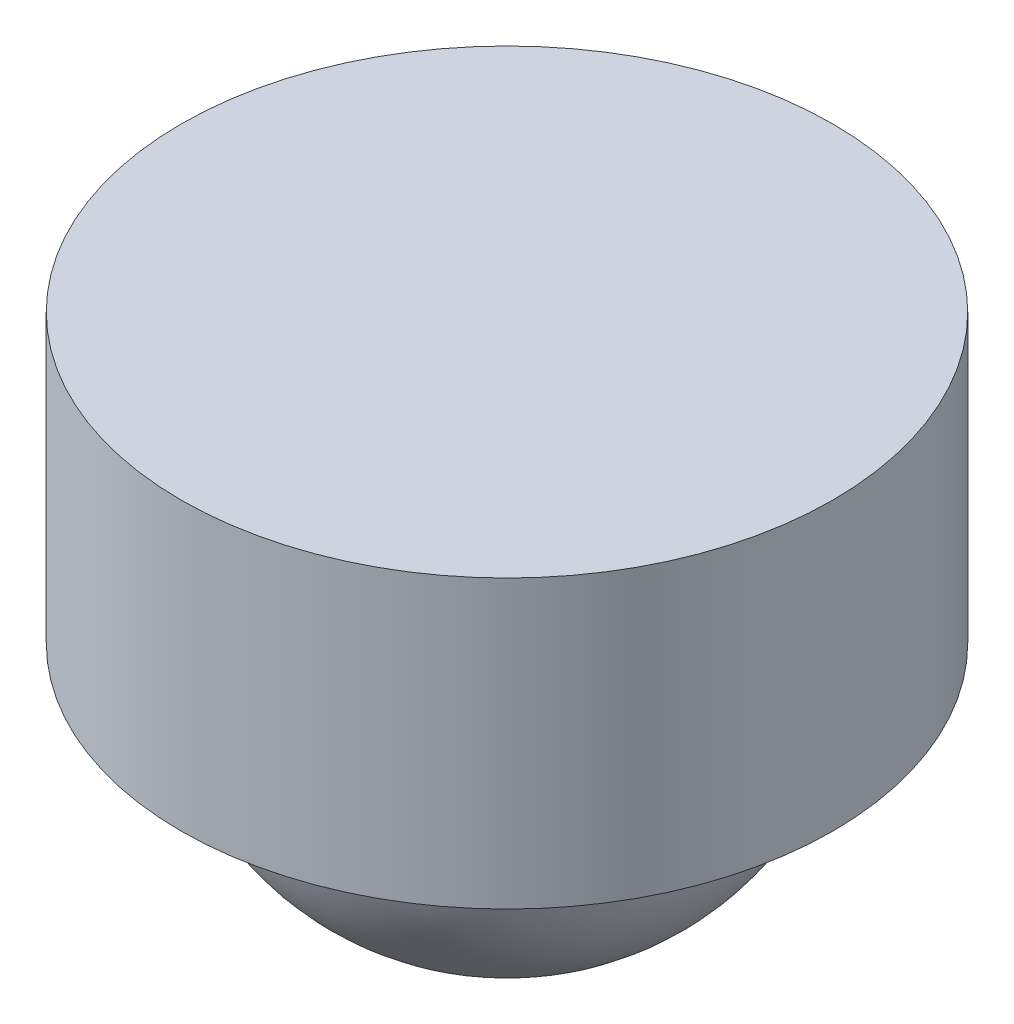
SolidWorks part; units mm, degrees
ref_plane "Front Plane" through (0, 0, 0) normal (0, 0, 1) x (1, 0, 0)
ref_plane "Top Plane" through (0, 0, 0) normal (0, 1, 0) x (1, 0, 0)
ref_plane "Right Plane" through (0, 0, 0) normal (1, 0, 0) x (0, 0, -1)
sketch "Sketch1" plane through (0, 0, 0) normal (0, 0, 1) x (1, 0, 0)
  line L0 (0, 0) -> (0, 67.9988) construction
  line L1 (0, 19) -> (0, 0)
  arc A0 (0, 0) -> (0, 19) centre (0, 9.5) cw
  dimension "D1" = 9.5
  dimension "D2" = 19
revolve "Revolve1" add sketch "Sketch1" angle 360 about L0
ref_plane "Plane1" through (0, 9, 0) normal (0, 1, 0) x (1, 0, 0)
sketch "Sketch2" plane through (0, 9, 0) normal (0, 1, 0) x (1, 0, 0)
  circle A0 centre (0, 0) radius 12.5
  dimension "D1" = 25
extrude "Boss-Extrude1" add sketch "Sketch2" along normal blind 11 separate body
